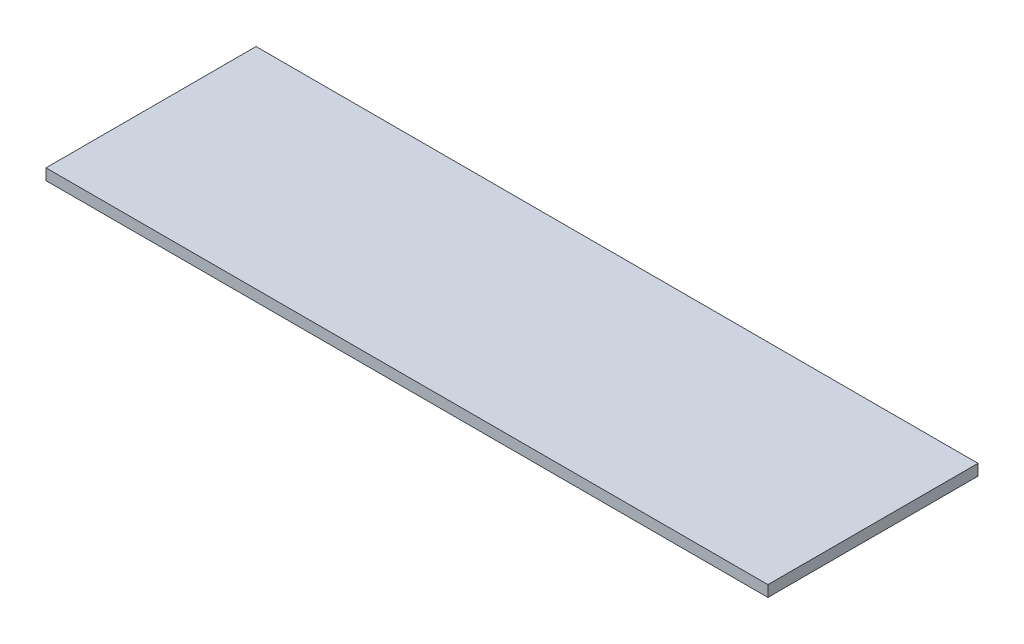
SolidWorks part; units mm, degrees
ref_plane "Front Plane" through (0, 0, 0) normal (0, 0, 1) x (1, 0, 0)
ref_plane "Top Plane" through (0, 0, 0) normal (0, 1, 0) x (1, 0, 0)
ref_plane "Right Plane" through (0, 0, 0) normal (1, 0, 0) x (0, 0, -1)
sketch "Sketch1" plane through (0, 0, 0) normal (0, 1, 0) x (1, 0, 0)
  line L1 (-59.1289, 61.5155) -> (249.8711, 61.5155)
  line L2 (-59.1289, 61.5155) -> (-59.1289, -28.4005)
  line L3 (-59.1289, -28.4005) -> (249.8711, -28.4005)
  line L4 (249.8711, 61.5155) -> (249.8711, -28.4005)
  dimension "D1" = 309
  dimension "D2" = 89.916
extrude "Boss-Extrude2" add sketch "Sketch1" along normal blind 4.7625
